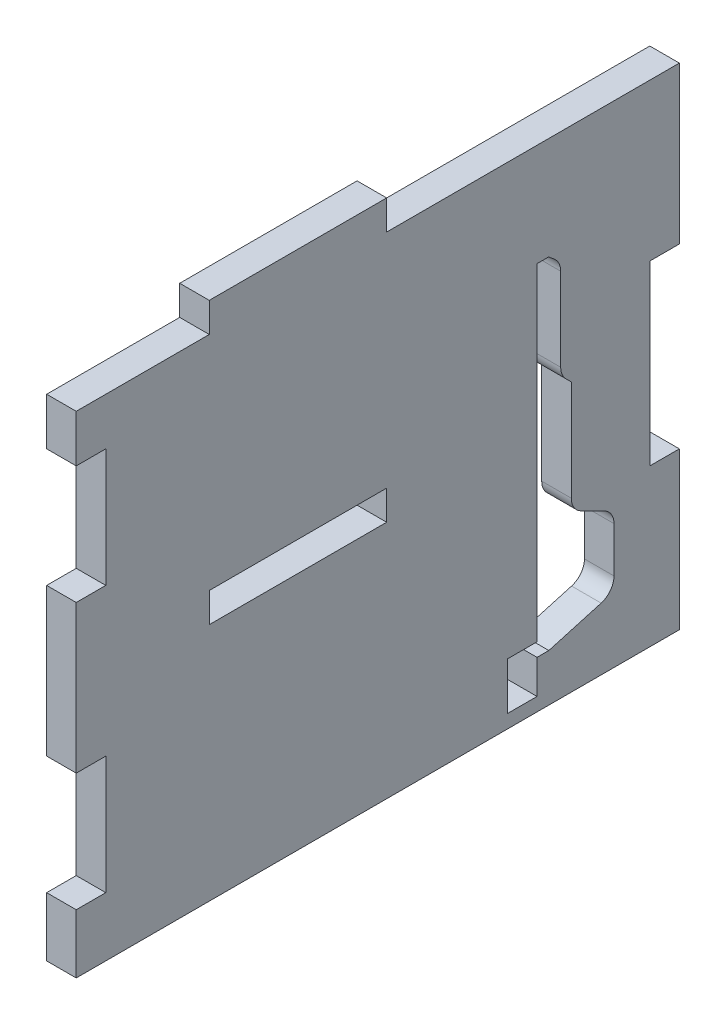
SolidWorks part; units mm, degrees
ref_plane "前视基准面" through (0, 0, 0) normal (0, 0, 1) x (1, 0, 0)
ref_plane "上视基准面" through (0, 0, 0) normal (0, 1, 0) x (1, 0, 0)
ref_plane "右视基准面" through (0, 0, 0) normal (1, 0, 0) x (0, 0, -1)
sketch "草图1" plane through (0, 0, 0) normal (1, 0, 0) x (0, 0, -1)
  line L0 (-71.7944, -30.468) -> (30.2056, -30.468)
  line L1 (-71.7944, -30.468) -> (-71.7944, -20.468)
  line L2 (-71.7944, 52.532) -> (-49.2944, 52.532)
  line L3 (-19.2944, 52.532) -> (30.2056, 52.532)
  line L5 (30.2056, -3.968) -> (30.2056, -30.468)
  line L6 (-49.2944, 52.532) -> (-49.2944, 57.532)
  line L7 (-49.2944, 57.532) -> (-19.2944, 57.532)
  line L8 (-19.2944, 52.532) -> (-19.2944, 57.532)
  line L9 (30.2056, 52.532) -> (30.2056, 26.032)
  line L10 (30.2056, 26.032) -> (25.2056, 26.032)
  line L17 (-49.2944, 15.032) -> (-19.2944, 15.032)
  line L21 (-71.7944, 44.532) -> (-71.7944, 52.532)
  line L22 (30.2056, -3.968) -> (25.2056, -3.968)
  line L23 (25.2056, 26.032) -> (25.2056, -3.968)
  line L24 (-71.7944, 44.532) -> (-66.7944, 44.532)
  line L25 (-71.7944, -0.468) -> (-71.7944, 24.532)
  line L26 (-71.7944, 24.532) -> (-66.7944, 24.532)
  line L27 (-66.7944, 44.532) -> (-66.7944, 24.532)
  line L28 (-71.7944, -20.468) -> (-66.7944, -20.468)
  line L38 (-49.2944, 15.032) -> (-49.2944, 10.032)
  line L39 (-71.7944, -0.468) -> (-66.7944, -0.468)
  line L56 (-66.7944, -20.468) -> (-66.7944, -0.468)
  line L57 (-49.2944, 10.032) -> (-19.2944, 10.032)
  line L58 (-19.2944, 15.032) -> (-19.2944, 10.032)
  line L73 (6.1012, -20.1977) -> (6.1012, 35.19)
  line L86 (134.2109, 57.5312) -> (132.175, 55.8231) construction
  line L87 (132.175, 55.8231) -> (132.175, 39.1122) construction
  line L88 (132.175, 39.1122) -> (130.386, 37.3231) construction
  line L89 (130.386, 37.3231) -> (130.386, 18.4366) construction
  line L90 (130.386, 18.4366) -> (123.1565, 14.7984) construction
  line L91 (123.1565, 14.7984) -> (123.1565, 3.0139) construction
  line L92 (123.1565, 3.0139) -> (134.2109, -0.1268) construction
  line L93 (136.2109, -0.1268) -> (136.2109, 57.5312) construction
  line L94 (134.2109, 57.5312) -> (136.2109, 57.5312) construction
  line L95 (134.2109, -0.1268) -> (136.2109, -0.1268) construction
  line L97 (8.1372, -22.468) -> (6.1372, -22.468)
  line L98 (8.1012, 35.19) -> (6.1012, 35.19)
  line L99 (16.978, -19.948) -> (8.1372, -22.468)
  line L100 (19.1556, -9.3915) -> (19.1556, -17.0629)
  line L101 (13.5775, -4.7356) -> (17.5042, -6.7117)
  line L102 (11.9261, 14.9819) -> (11.9261, -2.0558)
  line L103 (11.0157, 15.8923) -> (11.9261, 14.9819)
  line L104 (10.1371, 32.0829) -> (10.1371, 18.0137)
  line L105 (8.1012, 35.19) -> (9.0653, 34.3812)
  line L106 (19.2056, 58.9029) -> (19.2056, -44.6992) construction
  line L108 (-22.3047, -24.198) -> (35.0426, -24.198) construction
  line L114 (6.1372, -28.198) -> (1.1372, -28.198)
  line L115 (6.1372, -28.198) -> (6.1372, -22.468)
  line L116 (6.1012, -20.1977) -> (1.1372, -20.1977)
  line L117 (1.1372, -28.198) -> (1.1372, -20.1977)
  arc A0 (10.1371, 32.0829) -> (9.0653, 34.3812) centre (7.1371, 32.0829) ccw
  arc A1 (11.0157, 15.8923) -> (10.1371, 18.0137) centre (13.1371, 18.0137) cw
  arc A2 (13.5775, -4.7356) -> (11.9261, -2.0558) centre (14.9261, -2.0558) cw
  arc A3 (19.1556, -9.3915) -> (17.5042, -6.7117) centre (16.1556, -9.3915) ccw
  arc A4 (16.978, -19.948) -> (19.1556, -17.0629) centre (16.1556, -17.0629) ccw
  point P18 (10.1371, 33.4819)
  point P22 (10.1371, 16.771)
  point P39 (11.9261, -3.9046)
  point P45 (19.1556, -7.5428)
  point P50 (19.1556, -19.3273)
  dimension "D50" = 3
  dimension "D2" = 5
  dimension "D5" = 5
  dimension "D6" = 5
  dimension "D7" = 30
  dimension "D8" = 22.5
  dimension "D9" = 40.5
  dimension "D10" = 6.27
  dimension "D11" = 57.658
  dimension "D12" = 2
  dimension "D13" = 13.0544
  dimension "D14" = 5.825
  dimension "D15" = 83
  dimension "D16" = 4.0359
  dimension "D17" = 102
  dimension "D18" = 83
  dimension "D19" = 2
  dimension "D20" = 11.7845
  dimension "D21" = 18.8865
  dimension "D22" = 16.7109
  dimension "D23" = 3.1407
  dimension "D24" = 3.6382
  dimension "D25" = 1.7891
  dimension "D26" = 1.7081
  dimension "D28" = 11.7845
  dimension "D29" = 3.1407
  dimension "D30" = 3.6382
  dimension "D31" = 18.8865
  dimension "D32" = 5
  dimension "D33" = 30
  dimension "D34" = 22.5
  dimension "D35" = 26.5
  dimension "D36" = 30
  dimension "D37" = 5
  dimension "D38" = 10
  dimension "D39" = 1.7891
  dimension "D40" = 20
  dimension "D41" = 8
  dimension "D42" = 16.7109
  dimension "D43" = 1.7081
  dimension "D44" = 2
  dimension "D46" = 13.0544
  dimension "D47" = 5.825
  dimension "D48" = 4.0359
  dimension "D51" = 11
  dimension "D52" = 13.0544
  dimension "D53" = 0.1
  dimension "D59" = 4
extrude "凸台-拉伸1" add sketch "草图1" along normal blind 5
